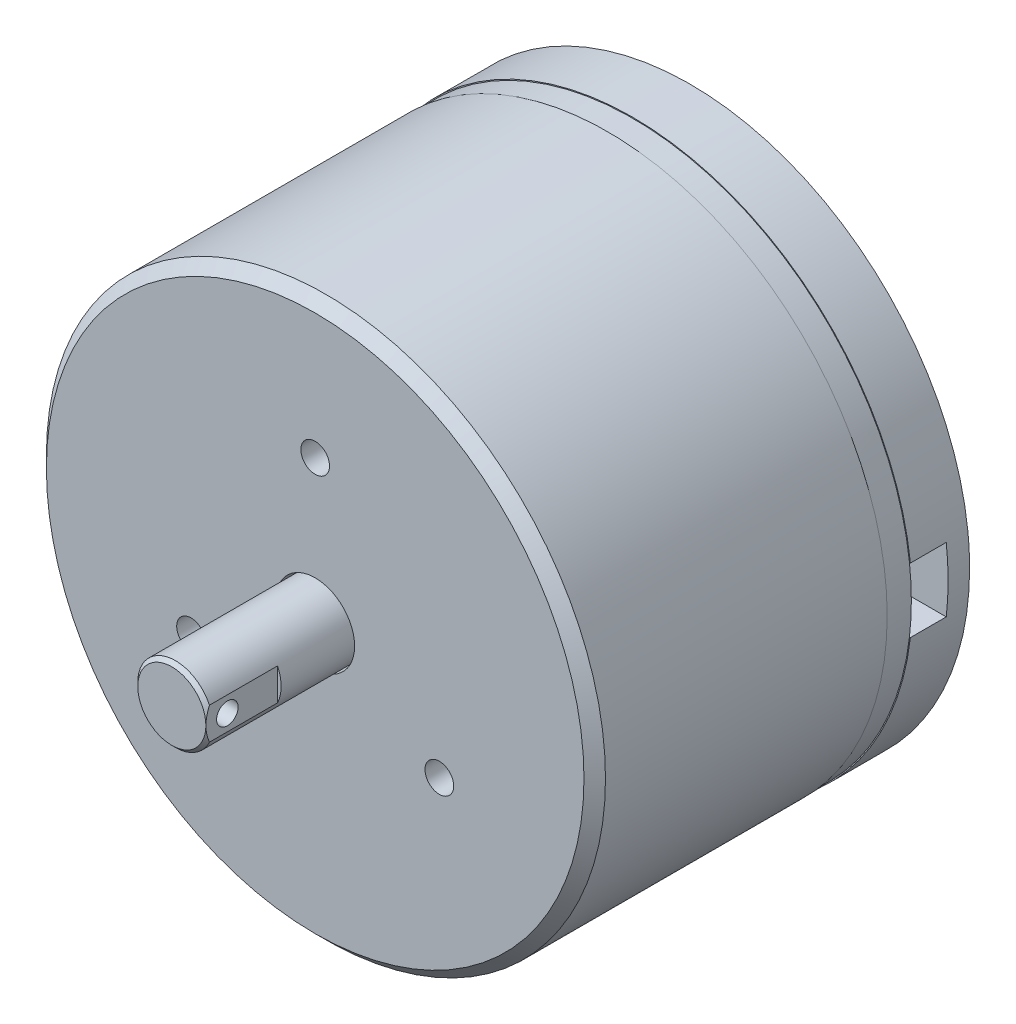
SolidWorks part; units mm, degrees
ref_plane "前视基准面" through (0, 0, 0) normal (0, 0, 1) x (1, 0, 0)
ref_plane "上视基准面" through (0, 0, 0) normal (0, 1, 0) x (1, 0, 0)
ref_plane "右视基准面" through (0, 0, 0) normal (1, 0, 0) x (0, 0, -1)
sketch "草图1" plane through (0, 0, 0) normal (0, 0, 1) x (1, 0, 0)
  circle A0 centre (0, 0) radius 39
extrude "凸台-拉伸1" add sketch "草图1" along normal blind 53.8
sketch "草图2" plane through (0, 0, 53.8) normal (0, 0, 1) x (1, 0, 0)
  circle A0 centre (0, 0) radius 20 construction
  circle A1 centre (0, 20) radius 2
  circle A2 centre (17.3205, -10) radius 2
  circle A3 centre (-17.3205, -10) radius 2
  point P11 (0, 0)
  dimension "D1" = 3
extrude "切除-拉伸1" cut sketch "草图2" against normal blind 3
sketch "草图3" plane through (0, 0, 53.8) normal (0, 0, 1) x (1, 0, 0)
  circle A0 centre (0, 0) radius 5.25
extrude "凸台-拉伸2" add sketch "草图3" along normal blind 20
sketch "草图4" plane through (0, 0, 53.8) normal (0, 0, 1) x (1, 0, 0)
  circle A0 centre (0, 0) radius 5.25
  circle A1 centre (0, 0) radius 5.5
extrude "切除-拉伸2" cut sketch "草图4" against normal blind 10
chamfer "倒角1" distance 0.5 angle 45 1 edges at (5.25, 0, 73.8)
sketch "草图5" plane through (0, 0, 73.8) normal (0, 0, 1) x (1, 0, 0)
  line L1 (4.75, 0) -> (4.75, 11.3065)
  line L2 (4.75, 11.3065) -> (10.5949, 11.3065)
  line L3 (10.5949, 11.3065) -> (10.5949, -9.4089)
  line L4 (10.5949, -9.4089) -> (4.75, -9.4089)
  line L5 (4.75, -9.4089) -> (4.75, 0)
extrude "切除-拉伸3" cut sketch "草图5" against normal blind 10
chamfer "倒角2" distance 1.5 angle 45 1 edges at (39, 0, 53.8)
sketch "草图6" plane through (0, 0, 0) normal (0, 1, 0) x (1, 0, 0)
  line L0 (-39, 0) -> (-39, -1.5)
  line L1 (-39, -1.5) -> (-33.5087, 0)
  line L2 (39, 0) -> (-39, 0) construction
  line L3 (-33.5087, 0) -> (-39, 0)
  line L4 (0, 0) -> (0, 8.006) construction
revolve "切除-旋转1" cut sketch "草图6" angle 360 about L4
ref_plane "基准面1" through (40, 0, 0) normal (1, 0, 0) x (0, 0, -1)
sketch "草图7" plane through (40, 0, 0) normal (1, 0, 0) x (0, 0, -1)
  line L0 (-1.5, 0) -> (-9.5, 0) construction
  line L1 (-1.5, 39) -> (-1.5, -39) construction
  line L2 (-9.5, -4.5) -> (-9.5, 4.5)
  line L3 (-9.5, 4.5) -> (-4.5, 4.5)
  line L4 (-4.5, 4.5) -> (-4.5, -4.5)
  line L5 (-9.5, -4.5) -> (-4.5, -4.5)
  point P10 (-4.5, 0)
extrude "切除-拉伸4" cut sketch "草图7" against normal blind 10
sketch "草图8" plane through (0, 0, 0) normal (0, 1, 0) x (1, 0, 0)
  line L1 (39, -9.5) -> (38.8698, -9.5)
  line L2 (39, -9.5) -> (38.7395, -9.5) construction
  line L3 (38.8698, -9.5) -> (38.8698, -13)
  line L4 (38.8698, -13) -> (39, -13)
  line L5 (39, -52.3) -> (39, -9.5) construction
  line L6 (39, -13) -> (39, -9.5)
  line L7 (0, 0) -> (0, -17.4932) construction
revolve "切除-旋转2" cut sketch "草图8" angle 360 about L7
sketch "草图9" plane through (4.75, 0, 0) normal (1, 0, 0) x (0, 0, -1)
  line L0 (-53.8, 0) -> (-70.8, 0)
  line L1 (-53.8, 37.5) -> (-53.8, -37.5) construction
  circle A0 centre (-70.8, 0) radius 1.5
extrude "切除-拉伸5" cut sketch "草图9" against normal blind 10
